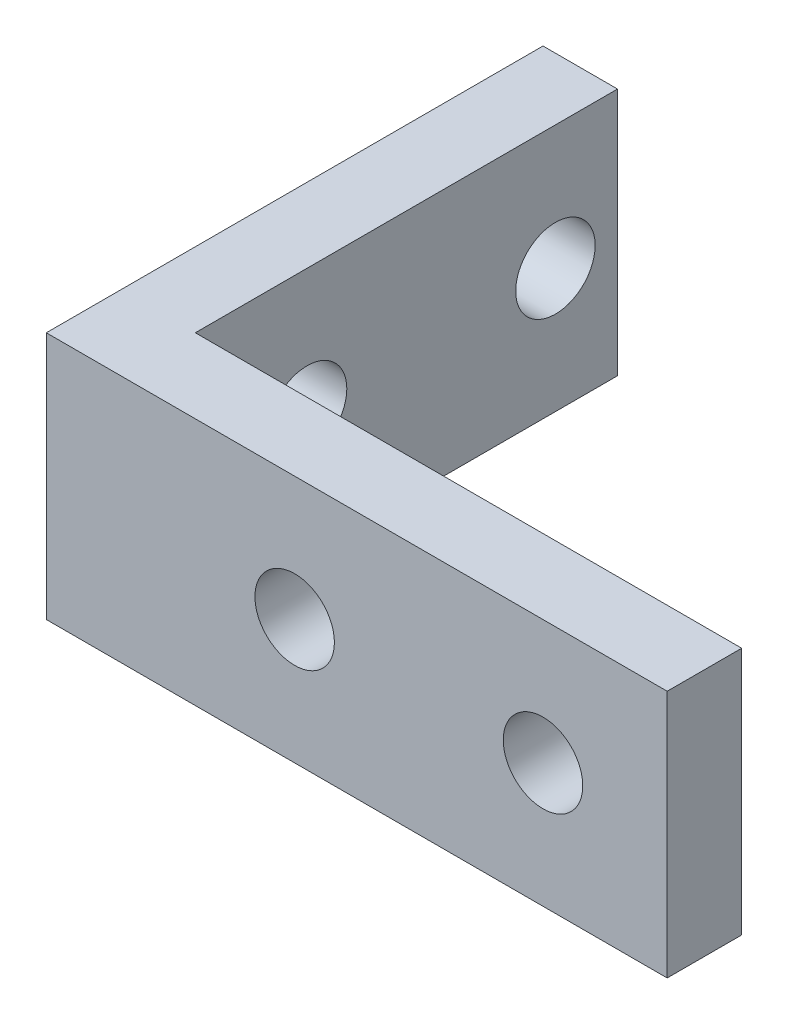
SolidWorks part; units mm, degrees
ref_plane "Front Plane" through (0, 0, 0) normal (0, 0, 1) x (1, 0, 0)
ref_plane "Top Plane" through (0, 0, 0) normal (0, 1, 0) x (1, 0, 0)
ref_plane "Right Plane" through (0, 0, 0) normal (1, 0, 0) x (0, 0, -1)
sketch "Sketch1" plane through (0, 0, 0) normal (0, 1, 0) x (1, 0, 0)
  line L0 (0, 0) -> (0, 20)
  line L1 (0, 20) -> (3, 20)
  line L2 (3, 20) -> (3, 3)
  line L3 (3, 3) -> (25, 3)
  line L4 (25, 3) -> (25, 0)
  line L5 (25, 0) -> (0, 0)
  dimension "D1" = 25
  dimension "D2" = 20
  dimension "D3" = 3
  dimension "D4" = 3
extrude "Boss-Extrude2" add sketch "Sketch1" along normal blind 10
sketch "Sketch2" plane through (0, 0, 0) normal (0, 0, 1) x (1, 0, 0)
  line L0 (0, 0) -> (25, 0) construction
  line L1 (0, 5) -> (25, 5) construction
  line L2 (0, 10) -> (0, 0) construction
  line L3 (25, 10) -> (25, 0) construction
  line L4 (12.5, 10) -> (12.5, 0) construction
  line L5 (0, 10) -> (25, 10) construction
  circle A0 centre (20, 5) radius 1.6
  circle A1 centre (10, 5) radius 1.6
  dimension "D1" = 3.2
  dimension "D2" = 3.2
  dimension "D3" = 5
  dimension "D4" = 10
  dimension "D5" = 10
extrude "Cut-Extrude1" cut sketch "Sketch2" against normal blind 10
sketch "Sketch3" plane through (3, 0, 0) normal (1, 0, 0) x (0, 0, -1)
  line L0 (20, 5) -> (3, 5) construction
  line L1 (20, 10) -> (20, 0) construction
  line L2 (3, 10) -> (3, 0) construction
  line L3 (11.5, 10) -> (11.5, 0) construction
  line L4 (3, 10) -> (20, 10) construction
  line L5 (3, 0) -> (20, 0) construction
  line L6 (0, 10) -> (0, 0) construction
  circle A0 centre (7.5, 5) radius 1.6
  circle A1 centre (17.5, 5) radius 1.6
  dimension "D1" = 3.2
  dimension "D3" = 3.2
  dimension "D2" = 0
  dimension "D4" = 0
  dimension "D5" = 10
  dimension "D6" = 7.5
extrude "Cut-Extrude2" cut sketch "Sketch3" against normal blind 10
